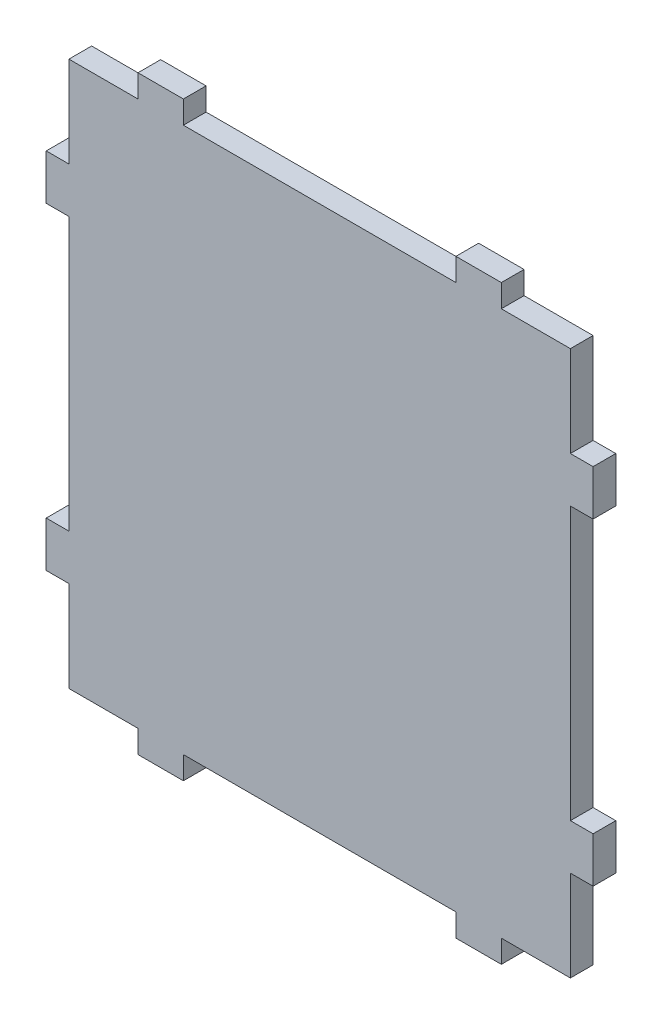
SolidWorks part; units mm, degrees
ref_plane "Front Plane" through (0, 0, 0) normal (0, 0, 1) x (1, 0, 0)
ref_plane "Top Plane" through (0, 0, 0) normal (0, 1, 0) x (1, 0, 0)
ref_plane "Right Plane" through (0, 0, 0) normal (1, 0, 0) x (0, 0, -1)
sketch "Sketch1" plane through (0, 0, 0) normal (0, 0, 1) x (1, 0, 0)
  line L0 (16.002, 0) -> (54.102, 0)
  line L1 (0, 0) -> (9.652, 0)
  line L2 (0, 0) -> (0, -12.7)
  line L3 (0, -76.2) -> (9.652, -76.2)
  line L4 (70.104, -19.05) -> (70.104, -57.15)
  line L6 (9.652, 0) -> (9.652, 3.175)
  line L7 (9.652, 3.175) -> (16.002, 3.175)
  line L8 (16.002, 0) -> (16.002, 3.175)
  line L9 (0, -19.05) -> (0, -57.15)
  line L10 (54.102, 0) -> (54.102, 3.175)
  line L11 (54.102, 3.175) -> (60.452, 3.175)
  line L12 (60.452, 0) -> (60.452, 3.175)
  line L13 (70.104, -12.7) -> (73.279, -12.7)
  line L14 (70.104, -63.5) -> (70.104, -76.2)
  line L15 (70.104, -19.05) -> (73.279, -19.05)
  line L16 (73.279, -12.7) -> (73.279, -19.05)
  line L17 (70.104, -57.15) -> (73.279, -57.15)
  line L18 (60.452, -76.2) -> (70.104, -76.2)
  line L19 (70.104, -63.5) -> (73.279, -63.5)
  line L20 (73.279, -57.15) -> (73.279, -63.5)
  line L21 (16.002, -76.2) -> (54.102, -76.2)
  line L22 (54.102, -76.2) -> (54.102, -79.375)
  line L23 (54.102, -79.375) -> (60.452, -79.375)
  line L24 (60.452, -76.2) -> (60.452, -79.375)
  line L25 (0, -63.5) -> (0, -76.2)
  line L26 (9.652, -76.2) -> (9.652, -79.375)
  line L27 (9.652, -79.375) -> (16.002, -79.375)
  line L28 (16.002, -76.2) -> (16.002, -79.375)
  line L29 (0, -63.5) -> (-3.175, -63.5)
  line L30 (60.452, 0) -> (70.104, 0)
  line L31 (0, -57.15) -> (-3.175, -57.15)
  line L32 (-3.175, -63.5) -> (-3.175, -57.15)
  line L33 (0, -19.05) -> (-3.175, -19.05)
  line L34 (70.104, 0) -> (70.104, -12.7)
  line L35 (0, -12.7) -> (-3.175, -12.7)
  line L36 (-3.175, -19.05) -> (-3.175, -12.7)
  dimension "D3" = 9.652
  dimension "D4" = 6.35
  dimension "D5" = 3.175
  dimension "D6" = 6.35
  dimension "D7" = 3.175
  dimension "D8" = 38.1
  dimension "D9" = 3.175
  dimension "D10" = 6.35
  dimension "D11" = 3.175
  dimension "D12" = 3.175
  dimension "D13" = 6.35
  dimension "D14" = 12.7
  dimension "D15" = 6.35
  dimension "D16" = 3.175
  dimension "D17" = 9.652
  dimension "D18" = 6.35
  dimension "D19" = 9.652
  dimension "D20" = 3.175
  dimension "D21" = 3.175
  dimension "D22" = 6.35
  dimension "D23" = 12.7
  dimension "D24" = 12.7
  dimension "D25" = 6.35
  dimension "D26" = 12.7
  dimension "D27" = 3.175
  dimension "D28" = 38.1
  dimension "D29" = 38.1
  dimension "D30" = 38.1
extrude "Boss-Extrude1" add sketch "Sketch1" along normal blind 3.175 contours L36 L33 L2 L31 L32 L29 L3 L26 L27 L28 L22 L23 L24 L4 L19 L20 L17 L15 L16 L13 L1 L12 L11 L10 L8 L7 L6 L35
